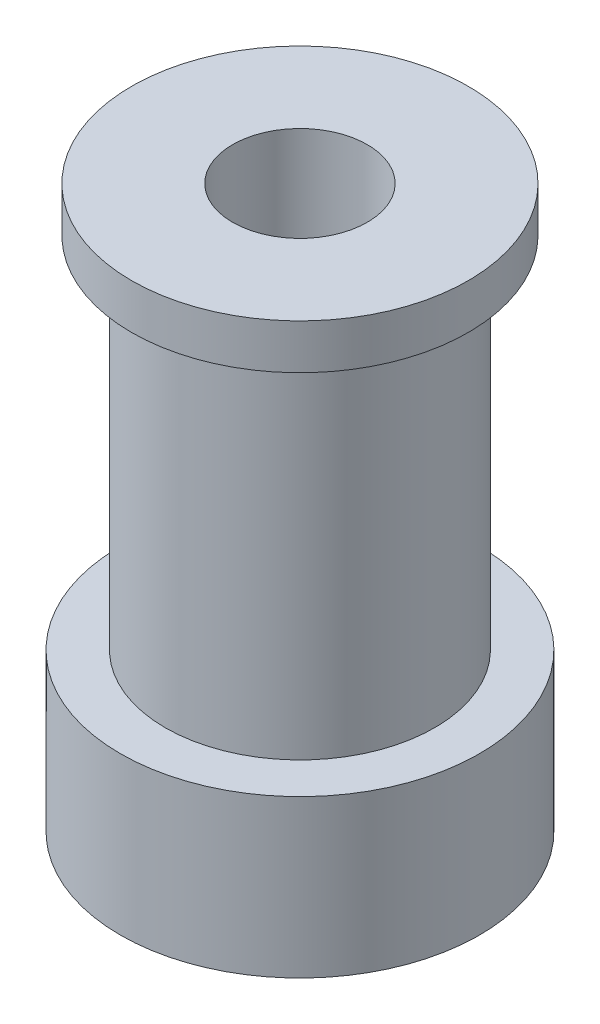
SolidWorks part; units mm, degrees
ref_plane "Front Plane" through (0, 0, 0) normal (0, 0, 1) x (1, 0, 0)
ref_plane "Top Plane" through (0, 0, 0) normal (0, 1, 0) x (1, 0, 0)
ref_plane "Right Plane" through (0, 0, 0) normal (1, 0, 0) x (0, 0, -1)
sketch "草图1" plane through (0, 0, 0) normal (0, 1, 0) x (1, 0, 0)
  circle A0 centre (0, 0) radius 8
  dimension "D1" = 16
extrude "凸台-拉伸1" add sketch "草图1" along normal blind 2 and the other way blind 5
sketch "草图2" plane through (0, 2, 0) normal (0, 1, 0) x (1, 0, 0)
  circle A0 centre (0, 0) radius 6
  dimension "D1" = 12
extrude "凸台-拉伸2" add sketch "草图2" along normal blind 16
sketch "草图3" plane through (0, 18, 0) normal (0, 1, 0) x (1, 0, 0)
  circle A0 centre (0, 0) radius 7.5
  dimension "D1" = 15
extrude "凸台-拉伸3" add sketch "草图3" along normal blind 2
sketch "草图4" plane through (0, 20, 0) normal (0, 1, 0) x (1, 0, 0)
  circle A0 centre (0, 0) radius 3
  dimension "D1" = 6
extrude "切除-拉伸1" cut sketch "草图4" against normal blind 34
ref_plane "基准面1" through (0, 10, 0) normal (0, 1, 0) x (1, 0, 0)
